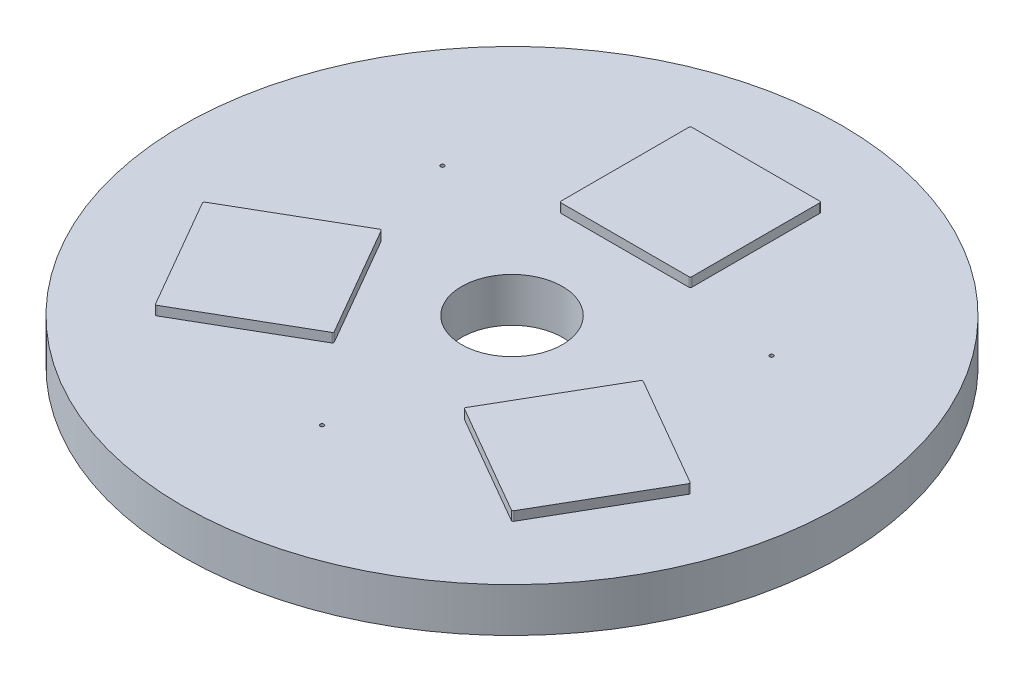
SolidWorks part; units mm, degrees
ref_plane "Front Plane" through (0, 0, 0) normal (0, 0, 1) x (1, 0, 0)
ref_plane "Top Plane" through (0, 0, 0) normal (0, 1, 0) x (1, 0, 0)
ref_plane "Right Plane" through (0, 0, 0) normal (1, 0, 0) x (0, 0, -1)
sketch "Sketch1" plane through (0, 0, 0) normal (0, 1, 0) x (1, 0, 0)
  circle A0 centre (0, 0) radius 26.1
  dimension "D1" = 52.2
extrude "Boss-Extrude1" add sketch "Sketch1" along normal mid plane 3.4925
sketch "Sketch3" plane through (0, 0, 0) normal (0, 1, 0) x (1, 0, 0)
  circle A0 centre (0, -15.0462) radius 0.1536
  circle A1 centre (0, 0) radius 3.9925
  dimension "D1" = 0.3071
  dimension "D3" = 7.985
  dimension "D2" = 15.0462
extrude "Cut-Extrude1" cut sketch "Sketch3" against normal through all both and the other way through all
pattern_circular "CirPattern1" count 3 over 360 about axis through (0, 0, 0) along (0, 1, 0) of "Cut-Extrude1"
sketch "Sketch5" plane through (0, 1.7463, 0) normal (0, 1, 0) x (1, 0, 0)
  line L0 (0, 0) -> (-16.7207, -9.6537) construction
  line L1 (-10.4377, -0.0432) -> (-19.2106, -5.1082)
  line L2 (-10.2787, -0.0858) -> (-5.2136, -8.8587)
  line L3 (-5.2563, -9.0177) -> (-14.0291, -14.0827)
  line L4 (-19.2532, -5.2673) -> (-14.1882, -14.0401)
  line L5 (0, 0) -> (0, -5.0148) construction
  arc A0 (-10.4377, -0.0432) -> (-10.2787, -0.0858) centre (-10.3795, -0.144) cw
  arc A1 (-5.2136, -8.8587) -> (-5.2563, -9.0177) centre (-5.3145, -8.9169) cw
  arc A2 (-14.0291, -14.0827) -> (-14.1882, -14.0401) centre (-14.0874, -13.9819) cw
  arc A3 (-19.2106, -5.1082) -> (-19.2532, -5.2673) centre (-19.1524, -5.209) ccw
  point P6 (-9.6427, -11.5502)
  dimension "D1" = 0.1164
  dimension "D3" = 10.3629
  dimension "D2" = 60
  dimension "D4" = 15.0462
extrude "Boss-Extrude2" add sketch "Sketch5" along normal blind 0.7276
pattern_circular "CirPattern2" count 3 over 360 about axis through (0, 0, 0) along (0, 1, 0) of "Boss-Extrude2"
mirror "Mirror1" about plane through (0, 0, 0) normal (0, 1, 0) of "CirPattern2", "Boss-Extrude2"
equation "\"D1@Sketch1\"=(\"Upper_Mount_largest_radius\"*2)-1mm"
equation "\"Piston_orifice_dia\"=0.30711"
equation "\"D1@Sketch3\"=\"Piston_orifice_dia\""
equation "\"Upper_Mount_largest_radius\" =26.6"
equation "\"Lower_Mount_piston_rod_radius\"\t=3.4925"
equation "\"D3@Sketch3\"=(\"Lower_Mount_piston_rod_radius\"*2)+1mm"
equation "\"D1@Boss-Extrude1\"=\"Lower_Mount_piston_rod_radius\""
equation "\"D2@Sketch3\"=(((\"Upper_Mount_largest_radius\"-0.5mm)-(\"Lower_Mount_piston_rod_radius\"+0.5mm))/2)+(\"Lower_Mount_piston_rod_radius\"+0.5mm)"
equation "\"D1@Boss-Extrude2\"=\"Lower_Mount_piston_rod_radius\"/4.8"
equation "\"Upper_mount_wall_thickness\" =4"
equation "\"Lower_Mount_piston_rod_length\" =149"
equation "\"Spring_inner_dia\" =80"
equation "\"Spring_wire_dia\" =8"
equation "\"D4@Sketch5\"=(((\"Upper_Mount_largest_radius\"-0.5mm)-(\"Lower_Mount_piston_rod_radius\"+0.5mm))/2)+(\"Lower_Mount_piston_rod_radius\"+0.5mm)"
equation "\"D1@Sketch5\"=\"Lower_Mount_piston_rod_radius\"/30"
equation "\"D3@Sketch5\"=((\"Upper_Mount_largest_radius\"-0.5mm)-(\"Lower_Mount_piston_rod_radius\"+0.5mm))/2.133333333333333333333333"
